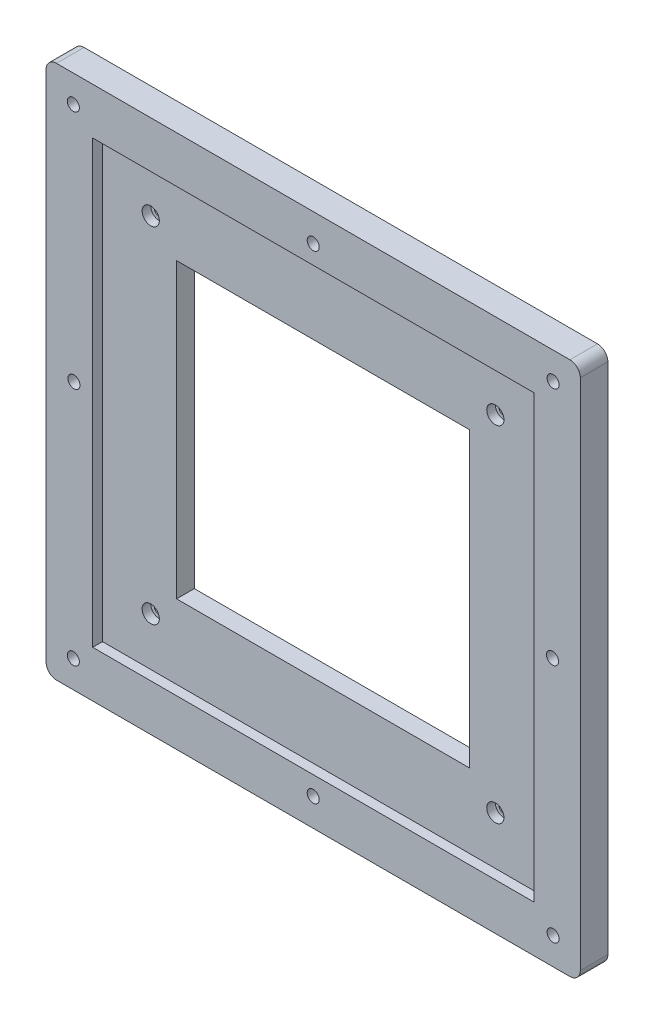
SolidWorks part; units mm, degrees
ref_plane "Спереди" through (0, 0, 0) normal (0, 0, 1) x (1, 0, 0)
ref_plane "Сверху" through (0, 0, 0) normal (0, 1, 0) x (1, 0, 0)
ref_plane "Справа" through (0, 0, 0) normal (1, 0, 0) x (0, 0, -1)
sketch "Sketch1" plane through (0, 0, 0) normal (0, 0, 1) x (1, 0, 0)
  line L1 (-63.5, 63.5) -> (63.5, 63.5) construction
  line L2 (-63.5, 63.5) -> (-63.5, -63.5) construction
  line L3 (-63.5, -63.5) -> (63.5, -63.5) construction
  line L4 (63.5, 63.5) -> (63.5, -63.5) construction
  line L5 (-63.5, 63.5) -> (63.5, -63.5) construction
  line L6 (-63.5, -63.5) -> (63.5, 63.5) construction
  line L7 (-77.5, 77.5) -> (77.5, 77.5)
  line L8 (-77.5, 77.5) -> (-77.5, -77.5)
  line L9 (-77.5, -77.5) -> (77.5, -77.5)
  line L10 (77.5, 77.5) -> (77.5, -77.5)
  line L11 (-77.5, 77.5) -> (77.5, -77.5) construction
  line L12 (-77.5, -77.5) -> (77.5, 77.5) construction
  line L17 (-42.5, 42.5) -> (42.5, 42.5)
  line L18 (-42.5, 42.5) -> (-42.5, -42.5)
  line L19 (-42.5, -42.5) -> (42.5, -42.5)
  line L20 (42.5, 42.5) -> (42.5, -42.5)
  line L21 (-42.5, 42.5) -> (42.5, -42.5) construction
  line L22 (-42.5, -42.5) -> (42.5, 42.5) construction
  line L23 (-50, 50) -> (50, 50) construction
  line L24 (-50, 50) -> (-50, -50) construction
  line L25 (-50, -50) -> (50, -50) construction
  line L26 (50, 50) -> (50, -50) construction
  line L27 (-50, 50) -> (50, -50) construction
  line L28 (-50, -50) -> (50, 50) construction
  circle A0 centre (-50, 50) radius 1.5
  circle A1 centre (50, 50) radius 1.5
  circle A2 centre (50, -50) radius 1.5
  circle A3 centre (-50, -50) radius 1.5
  point P0 (0, 0)
  point P6 (0, 0)
  point P11 (0, 0)
  point P12 (0, 0)
  point P17 (0, 0)
  point P32 (0, 0)
  dimension "D1" = 127
  dimension "D2" = 155
  dimension "D3" = 85
  dimension "D4" = 100
  dimension "D5" = 4
extrude "Boss-Extrude1" add sketch "Sketch1" along normal blind 8
sketch "Sketch3" plane through (0, 0, 8) normal (0, 0, 1) x (1, 0, 0)
  line L1 (-64, 64) -> (64, 64)
  line L2 (-64, 64) -> (-64, -64)
  line L3 (-64, -64) -> (64, -64)
  line L4 (64, 64) -> (64, -64)
  line L5 (-64, 64) -> (64, -64) construction
  line L6 (-64, -64) -> (64, 64) construction
  point P0 (0, 0)
  dimension "D1" = 128
extrude "Cut-Extrude2" cut sketch "Sketch3" against normal blind 2.85
fillet "Fillet1" radius 3 4 edges at (-77.5, -77.5, 4) (77.5, -77.5, 4) (77.5, 77.5, 4) (-77.5, 77.5, 4)
sketch "Sketch4" plane through (0, 0, 5.15) normal (0, 0, -1) x (-1, 0, 0)
  circle A0 centre (-50, 50) radius 2.5
  circle A1 centre (50, 50) radius 2.5
  circle A2 centre (50, -50) radius 2.5
  circle A3 centre (-50, -50) radius 2.5
  point P3 (0, 0)
  point P12 (0, 0)
  dimension "D1" = 4
extrude "Cut-Extrude3" cut sketch "Sketch4" along normal blind 2.5
sketch "Sketch5" plane through (0, 0, 8) normal (0, 0, 1) x (1, 0, 0)
  line L0 (0, 0) -> (0, 69.4313) construction
  line L1 (0, 0) -> (-69.6102, 69.6102) construction
  circle A0 centre (0, 69.4313) radius 1.75
  circle A1 centre (-69.6102, 69.6102) radius 1.75
  circle A2 centre (69.4313, 0) radius 1.75
  circle A3 centre (69.6102, 69.6102) radius 1.75
  circle A4 centre (0, -69.4313) radius 1.75
  circle A5 centre (69.6102, -69.6102) radius 1.75
  circle A6 centre (-69.4313, 0) radius 1.75
  circle A7 centre (-69.6102, -69.6102) radius 1.75
  point P23 (0, 0)
  dimension "D1" = 4
extrude "Cut-Extrude4" cut sketch "Sketch5" against normal blind 23
sketch "Sketch6" plane through (0, 0, 0) normal (0, 0, -1) x (-1, 0, 0)
  circle A0 centre (-69.6102, 69.6102) radius 3.35
  circle A1 centre (69.6102, 69.6102) radius 3.35
  circle A2 centre (69.6102, -69.6102) radius 3.35
  circle A3 centre (-69.6102, -69.6102) radius 3.35
  circle A4 centre (-69.4313, 0) radius 3.35
  circle A5 centre (0, 69.4313) radius 3.35
  circle A6 centre (69.4313, 0) radius 3.35
  circle A7 centre (0, -69.4313) radius 3.35
  point P12 (0, 0)
  point P22 (0, 0)
  dimension "D1" = 4
  dimension "D2" = 4
extrude "Cut-Extrude5" cut sketch "Sketch6" against normal blind 3.5
